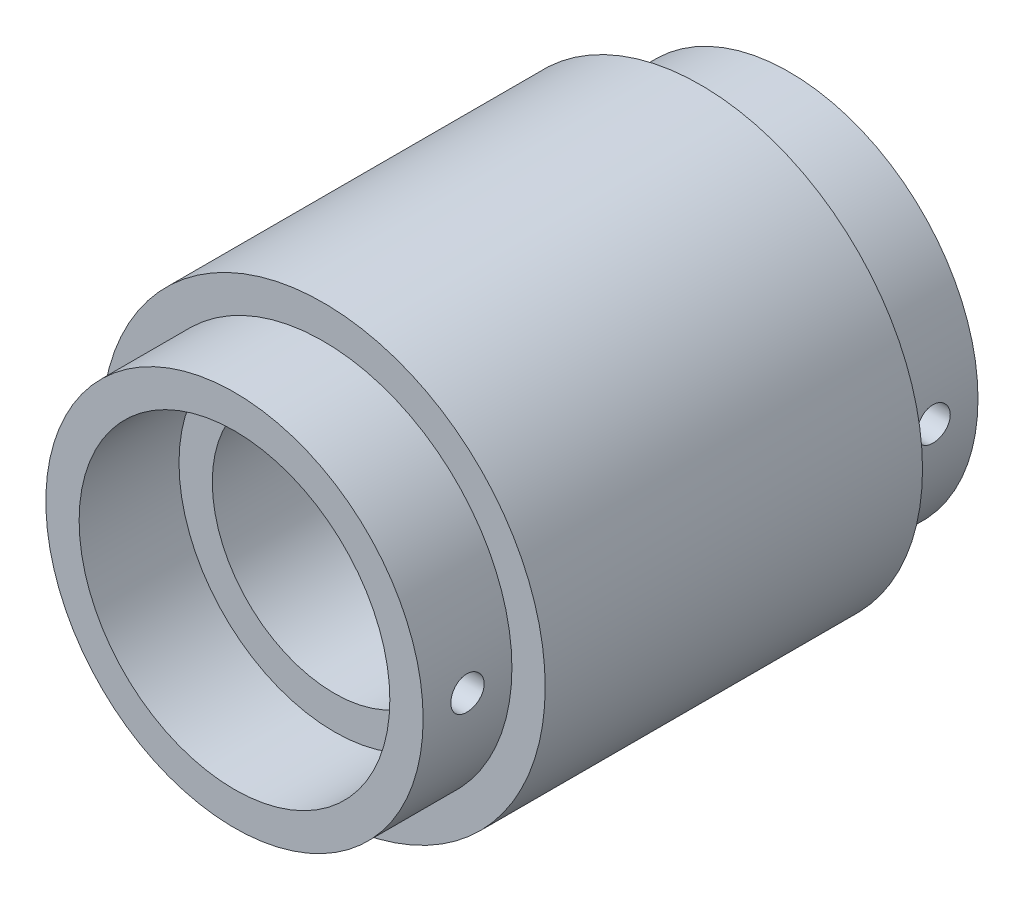
SolidWorks part; units mm, degrees
ref_plane "Płaszczyzna przednia" through (0, 0, 0) normal (0, 0, 1) x (1, 0, 0)
ref_plane "Płaszczyzna górna" through (0, 0, 0) normal (0, 1, 0) x (1, 0, 0)
ref_plane "Płaszczyzna prawa" through (0, 0, 0) normal (1, 0, 0) x (0, 0, -1)
sketch "Sketch1" plane through (0, 0, 0) normal (0, 0, 1) x (1, 0, 0)
  circle A0 centre (0, 0) radius 20
  dimension "D1" = 40
extrude "Boss-Extrude1" add sketch "Sketch1" along normal mid plane 50
hole_wizard "Hole1" positions "Sketch2" profile "Sketch3" legacy end condition through all
sketch "Sketch2" plane through (0, 0, 25) normal (0, 0, 1) x (1, 0, 0)
  point P0 (0, 0)
sketch "Sketch3" plane through (0, 0, 25) normal (1, 0, 0) x (0, -1, 0)
  line L0 (0, 0) -> (0, 56.6095)
  line L1 (0, 56.6095) -> (11, 50)
  line L2 (11, 50) -> (11, 9)
  line L3 (11, 9) -> (14, 9)
  line L4 (14, 0) -> (0, 0)
  line L5 (0, -11.3109) -> (0, 121.1557) construction
  line L6 (0, 56.6095) -> (-11, 50) construction
  line L7 (14, 9) -> (14, 0)
  dimension "Depth" = 50
  dimension "Drill Angle" = 118
  dimension "Diameter" = 22
  dimension "C-Bore Diameter" = 28
  dimension "C-Bore Depth" = 9
sketch "Sketch4" plane through (0, 0, 25) normal (0, 0, 1) x (1, 0, 0)
  circle A0 centre (0, 0) radius 20
  circle A1 centre (0, 0) radius 17
  circle A2 centre (0, 0) radius 20 construction
  dimension "D1" = 3
extrude "Cut-Extrude1" cut sketch "Sketch4" against normal blind 8
mirror "Mirror2" about plane through (0, 0, 0) normal (0, 0, 1) of "Cut-Extrude1", "Hole1"
sketch "Sketch5" plane through (0, 0, 0) normal (1, 0, 0) x (0, 0, -1)
  line L0 (-21, 0) -> (21, 0) construction
  line L3 (-25, 17) -> (-25, -17) construction
  circle A0 centre (-21, 0) radius 1.5
  circle A1 centre (21, 0) radius 1.5
  dimension "D2" = 3
  dimension "D3" = 3
  dimension "D1" = 4
extrude "Cut-Extrude2" cut sketch "Sketch5" along normal up to surface (17 mm away) up to face at (17, 0, -17)
